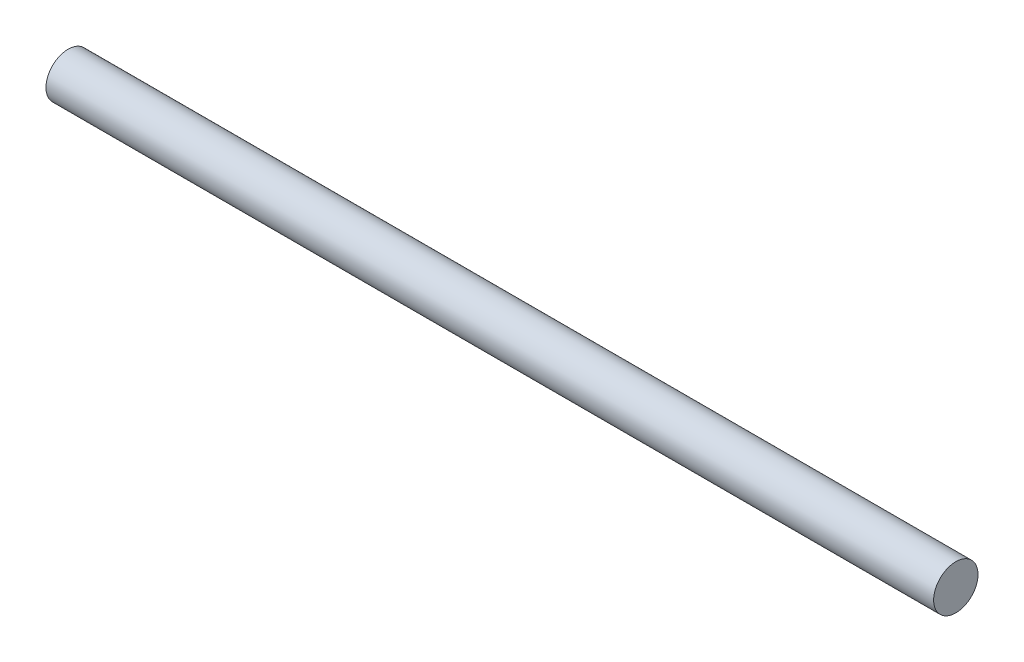
SolidWorks part; units mm, degrees
ref_plane "Front Plane" through (0, 0, 0) normal (0, 0, 1) x (1, 0, 0)
ref_plane "Top Plane" through (0, 0, 0) normal (0, 1, 0) x (1, 0, 0)
ref_plane "Right Plane" through (0, 0, 0) normal (1, 0, 0) x (0, 0, -1)
sketch "Sketch1" plane through (0, 0, 0) normal (1, 0, 0) x (0, 0, -1)
  circle A0 centre (0, 0) radius 2
  dimension "D1" = 4
extrude "Boss-Extrude1" add sketch "Sketch1" along normal blind 80
